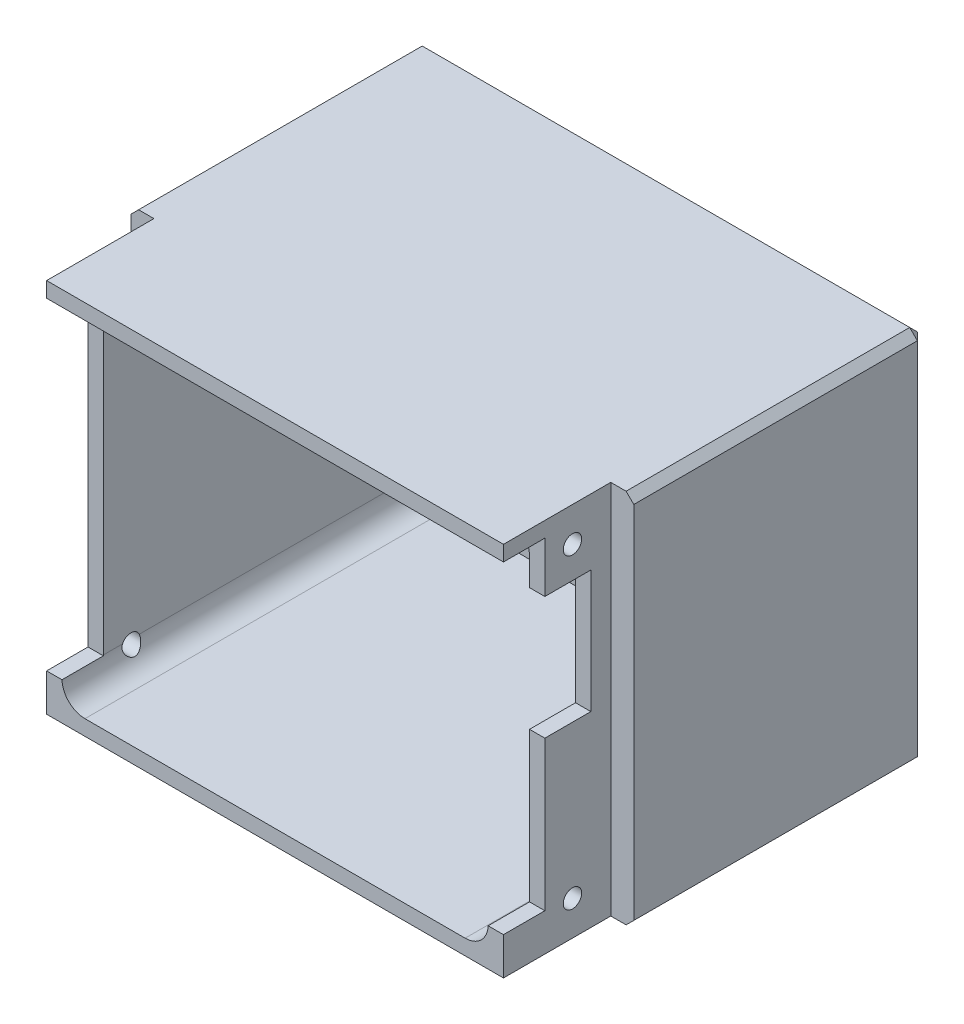
SolidWorks part; units mm, degrees
ref_plane "Front Plane" through (0, 0, 0) normal (0, 0, 1) x (1, 0, 0)
ref_plane "Top Plane" through (0, 0, 0) normal (0, 1, 0) x (1, 0, 0)
ref_plane "Right Plane" through (0, 0, 0) normal (1, 0, 0) x (0, 0, -1)
sketch "Sketch7" plane through (0, 0, 0) normal (0, 0, 1) x (1, 0, 0)
  line L1 (-16.4, -12.25) -> (16.4, -12.25)
  line L2 (-16.4, -12.25) -> (-16.4, 12.25)
  line L3 (-16.4, 12.25) -> (16.4, 12.25)
  line L4 (16.4, -12.25) -> (16.4, 12.25)
  line L5 (-16.4, -12.25) -> (16.4, 12.25) construction
  line L6 (-16.4, 12.25) -> (16.4, -12.25) construction
  point P0 (0, 0)
  dimension "D1" = 24.5
  dimension "D2" = 32.8
extrude "Boss-Extrude3" add sketch "Sketch7" along normal blind 19
sketch "Sketch8" plane through (0, 0, 19) normal (0, 0, 1) x (1, 0, 0)
  line L0 (16.4, 12.25) -> (-16.4, 12.25) construction
  line L1 (-14.9, -12.25) -> (14.9, -12.25)
  line L2 (-14.9, -12.25) -> (-14.9, 12.25)
  line L3 (-14.9, 12.25) -> (14.9, 12.25)
  line L4 (14.9, -12.25) -> (14.9, 12.25)
  line L5 (-14.9, -12.25) -> (14.9, 12.25) construction
  line L6 (-14.9, 12.25) -> (14.9, -12.25) construction
  point P0 (0, 0)
  dimension "D1" = 29.8
  dimension "D2" = 24.5
extrude "Boss-Extrude4" add sketch "Sketch8" along normal blind 7
sketch "Sketch10" plane through (-14.9, 0, 0) normal (-1, 0, 0) x (0, 0, 1)
  line L0 (26, 12.25) -> (26, -12.25) construction
  line L1 (26, 11.25) -> (23.3, 11.25)
  line L2 (26, 11.25) -> (26, -9.8)
  line L3 (26, -9.8) -> (23.3, -9.8)
  line L4 (23.3, 11.25) -> (23.3, -9.8)
  dimension "D1" = 2.7
  dimension "D2" = 21.05
sketch "Sketch16" plane through (0, 0, 26) normal (0, 0, 1) x (1, 0, 0)
  line L8 (-12.4, -11.25) -> (12.4, -11.25)
  line L9 (-13.9, -9.75) -> (-13.9, 9.75)
  line L10 (-12.4, 11.25) -> (12.4, 11.25)
  line L11 (13.9, -9.75) -> (13.9, 9.75)
  line L12 (-13.9, -11.25) -> (13.9, 11.25) construction
  line L13 (-13.9, 11.25) -> (13.9, -11.25) construction
  arc A0 (-13.9, -9.75) -> (-12.4, -11.25) centre (-12.4, -9.75) ccw
  arc A1 (12.4, -11.25) -> (13.9, -9.75) centre (12.4, -9.75) ccw
  arc A2 (13.9, 9.75) -> (12.4, 11.25) centre (12.4, 9.75) ccw
  arc A3 (-12.4, 11.25) -> (-13.9, 9.75) centre (-12.4, 9.75) ccw
  point P10 (0, 0)
  dimension "D1" = 1.5
  dimension "D3" = 27.8
  dimension "D4" = 22.5
extrude "Cut-Extrude1" cut sketch "Sketch16" against normal blind 23.5 contours L8 A1 L11 A2 L10 A3 L9 A0
extrude "Cut-Extrude2" cut sketch "Sketch10" against normal up to surface (29.8 mm away) contours L4 L3 L2 L1 up to face at (14.9, 0, 22.5)
sketch "Sketch18" plane through (14.9, 0, 0) normal (1, 0, 0) x (0, 0, -1)
  line L0 (-23.3, -9.8) -> (-23.3, 11.25) construction
  line L1 (-23.3, 7.95) -> (-20.3, 7.95)
  line L2 (-23.3, 7.95) -> (-23.3, -0.05)
  line L3 (-23.3, -0.05) -> (-20.3, -0.05)
  line L4 (-20.3, 7.95) -> (-20.3, -0.05)
  dimension "D1" = 8
  dimension "D2" = 3
extrude "Cut-Extrude3" cut sketch "Sketch18" against normal up to surface (1 mm away) up to face at (13.9, 0, 12.9)
chamfer "Chamfer1" distance 0.5 angle 45 8 edges at (-16.4, 12.25, 9.5) (-16.4, 0, 0) (-16.4, -12.25, 9.5) (16.4, -12.25, 9.5) (0, -12.25, 0) (0, 12.25, 0) (16.4, 0, 0) (16.4, 12.25, 9.5)
sketch "Sketch19" plane through (-14.9, 0, 0) normal (-1, 0, 0) x (0, 0, 1)
  circle A0 centre (21.5, 10) radius 0.6
  circle A1 centre (21.5, -10) radius 0.6
sketch "Sketch20" plane through (14.9, 0, 0) normal (1, 0, 0) x (0, 0, -1)
  circle A0 centre (-21.5, 10) radius 0.6
  circle A1 centre (-21.5, -10) radius 0.6
extrude "Cut-Extrude5" cut sketch "Sketch20" against normal up to next
extrude "Cut-Extrude6" cut sketch "Sketch19" against normal up to next
sketch "Sketch21" plane through (0, 0, 0) normal (0, 0, -1) x (-1, 0, 0)
  line L0 (-15.9, 0) -> (15.9, 0) construction
  line L2 (0, 11.75) -> (0, -11.75) construction
  line L3 (15.9, 11.75) -> (-15.9, 11.75) construction
  line L4 (-15.9, -11.75) -> (15.9, -11.75) construction
  line L5 (-15.9, 11.75) -> (-15.9, -11.75) construction
  line L6 (15.9, -11.75) -> (15.9, 11.75) construction
  circle A0 centre (-10.65, 0) radius 2.25
  circle A1 centre (0, 6) radius 1.25
  circle A2 centre (0, -6) radius 1.25
  point P13 (0, 0)
  point P14 (0, 0)
  point P22 (0, 3.636)
  point P23 (0, 5.5988)
  dimension "D1" = 4.5
  dimension "D2" = 2.5
  dimension "D3" = 2.5
extrude "Cut-Extrude7" cut sketch "Sketch21" against normal up to next
chamfer "Chamfer2" distance 0.5 angle 45 1 edges at (8.4, 0, 0)
chamfer "Chamfer4" distance 0.2 angle 45 5 edges at (12.9, 0, 2.5) (1.25, -6, 2.5) (1.25, 6, 2.5) (-1.25, -6, 0) (-1.25, 6, 0)
